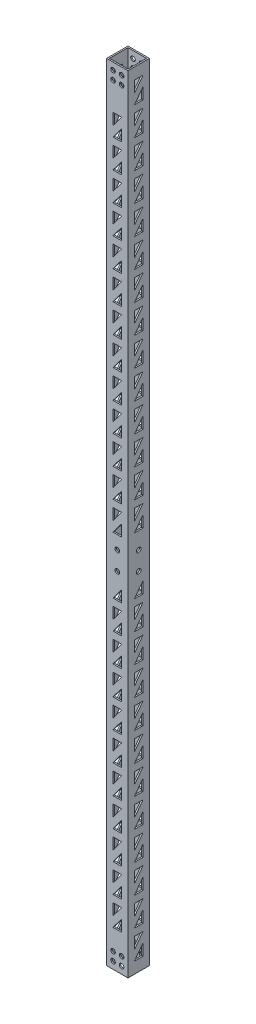
SolidWorks part; units mm, degrees
ref_plane "前视基准面" through (0, 0, 0) normal (0, 0, 1) x (1, 0, 0)
ref_plane "上视基准面" through (0, 0, 0) normal (0, 1, 0) x (1, 0, 0)
ref_plane "右视基准面" through (0, 0, 0) normal (1, 0, 0) x (0, 0, -1)
other "Configuration Table"
sketch "草图1" plane through (0, 0, 0) normal (0, 1, 0) x (1, 0, 0)
  line L1 (6.5, -6.5) -> (-6.5, -6.5)
  line L2 (6.5, -6.5) -> (6.5, 6.5)
  line L3 (6.5, 6.5) -> (-6.5, 6.5)
  line L4 (-6.5, -6.5) -> (-6.5, 6.5)
  line L5 (6.5, -6.5) -> (-6.5, 6.5) construction
  line L6 (6.5, 6.5) -> (-6.5, -6.5) construction
  line L7 (7.5, -7.5) -> (-7.5, -7.5)
  line L8 (7.5, -7.5) -> (7.5, 7.5)
  line L9 (7.5, 7.5) -> (-7.5, 7.5)
  line L10 (-7.5, -7.5) -> (-7.5, 7.5)
  line L11 (7.5, -7.5) -> (-7.5, 7.5) construction
  line L12 (7.5, 7.5) -> (-7.5, -7.5) construction
  point P0 (0, 0)
  point P6 (0, 0)
  dimension "D1" = 13
  dimension "D2" = 15
extrude "凸台-拉伸1" add sketch "草图1" along normal blind 551
sketch "草图2" plane through (0, 0, 7.5) normal (0, 0, 1) x (1, 0, 0)
  line L0 (-7.5, 543) -> (7.5, 543) construction
  line L1 (-7.5, 551) -> (-7.5, 0) construction
  line L2 (7.5, 551) -> (7.5, 0) construction
  line L3 (-7.5, 275.5) -> (7.5, 275.5) construction
  line L4 (-7.5, 551) -> (7.5, 551) construction
  line L5 (0, 549.2213) -> (0, 545.4151) construction
  line L6 (-7.5, 525.5) -> (7.5, 525.5) construction
  line L7 (-7.5, 25.5) -> (7.5, 25.5) construction
  line L8 (-3, 512.5) -> (-3, 520.5)
  line L9 (-3, 520.5) -> (3, 520.5)
  line L10 (3, 520.5) -> (-3, 512.5)
  line L11 (-3, 505.5) -> (3, 505.5)
  line L12 (3, 505.5) -> (3, 513.5)
  line L13 (3, 513.5) -> (-3, 505.5)
  line L14 (3, 500.5) -> (-3, 492.5)
  line L15 (-3, 492.5) -> (-3, 500.5)
  line L16 (-3, 500.5) -> (3, 500.5)
  line L17 (3, 493.5) -> (-3, 485.5)
  line L18 (-3, 485.5) -> (3, 485.5)
  line L19 (3, 485.5) -> (3, 493.5)
  line L20 (3, 480.5) -> (-3, 472.5)
  line L21 (-3, 472.5) -> (-3, 480.5)
  line L22 (-3, 480.5) -> (3, 480.5)
  line L23 (3, 473.5) -> (-3, 465.5)
  line L24 (-3, 465.5) -> (3, 465.5)
  line L25 (3, 465.5) -> (3, 473.5)
  line L26 (3, 460.5) -> (-3, 452.5)
  line L27 (-3, 452.5) -> (-3, 460.5)
  line L28 (-3, 460.5) -> (3, 460.5)
  line L29 (3, 453.5) -> (-3, 445.5)
  line L30 (-3, 445.5) -> (3, 445.5)
  line L31 (3, 445.5) -> (3, 453.5)
  line L32 (3, 440.5) -> (-3, 432.5)
  line L33 (-3, 432.5) -> (-3, 440.5)
  line L34 (-3, 440.5) -> (3, 440.5)
  line L35 (3, 433.5) -> (-3, 425.5)
  line L36 (-3, 425.5) -> (3, 425.5)
  line L37 (3, 425.5) -> (3, 433.5)
  line L38 (3, 420.5) -> (-3, 412.5)
  line L39 (-3, 412.5) -> (-3, 420.5)
  line L40 (-3, 420.5) -> (3, 420.5)
  line L41 (3, 413.5) -> (-3, 405.5)
  line L42 (-3, 405.5) -> (3, 405.5)
  line L43 (3, 405.5) -> (3, 413.5)
  line L44 (3, 400.5) -> (-3, 392.5)
  line L45 (-3, 392.5) -> (-3, 400.5)
  line L46 (-3, 400.5) -> (3, 400.5)
  line L47 (3, 393.5) -> (-3, 385.5)
  line L48 (-3, 385.5) -> (3, 385.5)
  line L49 (3, 385.5) -> (3, 393.5)
  line L50 (3, 380.5) -> (-3, 372.5)
  line L51 (-3, 372.5) -> (-3, 380.5)
  line L52 (-3, 380.5) -> (3, 380.5)
  line L53 (3, 373.5) -> (-3, 365.5)
  line L54 (-3, 365.5) -> (3, 365.5)
  line L55 (3, 365.5) -> (3, 373.5)
  line L56 (3, 360.5) -> (-3, 352.5)
  line L57 (-3, 352.5) -> (-3, 360.5)
  line L58 (-3, 360.5) -> (3, 360.5)
  line L59 (3, 353.5) -> (-3, 345.5)
  line L60 (-3, 345.5) -> (3, 345.5)
  line L61 (3, 345.5) -> (3, 353.5)
  line L62 (3, 340.5) -> (-3, 332.5)
  line L63 (-3, 332.5) -> (-3, 340.5)
  line L64 (-3, 340.5) -> (3, 340.5)
  line L65 (3, 333.5) -> (-3, 325.5)
  line L66 (-3, 325.5) -> (3, 325.5)
  line L67 (3, 325.5) -> (3, 333.5)
  line L68 (3, 320.5) -> (-3, 312.5)
  line L69 (-3, 312.5) -> (-3, 320.5)
  line L70 (-3, 320.5) -> (3, 320.5)
  line L71 (3, 313.5) -> (-3, 305.5)
  line L72 (-3, 305.5) -> (3, 305.5)
  line L73 (3, 305.5) -> (3, 313.5)
  line L74 (3, 300.5) -> (-3, 292.5)
  line L75 (-3, 292.5) -> (-3, 300.5)
  line L76 (-3, 300.5) -> (3, 300.5)
  line L77 (3, 293.5) -> (-3, 285.5)
  line L78 (-3, 285.5) -> (3, 285.5)
  line L79 (3, 285.5) -> (3, 293.5)
  line L80 (3, 280.5) -> (-3, 272.5)
  line L81 (-3, 272.5) -> (-3, 280.5)
  line L82 (-3, 280.5) -> (3, 280.5)
  line L83 (3, 273.5) -> (-3, 265.5)
  line L84 (-3, 265.5) -> (3, 265.5)
  line L85 (3, 265.5) -> (3, 273.5)
  line L95 (3, 233.5) -> (-3, 225.5)
  line L96 (-3, 225.5) -> (3, 225.5)
  line L97 (3, 225.5) -> (3, 233.5)
  line L98 (3, 220.5) -> (-3, 212.5)
  line L99 (-3, 212.5) -> (-3, 220.5)
  line L100 (-3, 220.5) -> (3, 220.5)
  line L101 (3, 213.5) -> (-3, 205.5)
  line L102 (-3, 205.5) -> (3, 205.5)
  line L103 (3, 205.5) -> (3, 213.5)
  line L104 (3, 200.5) -> (-3, 192.5)
  line L105 (-3, 192.5) -> (-3, 200.5)
  line L106 (-3, 200.5) -> (3, 200.5)
  line L107 (3, 193.5) -> (-3, 185.5)
  line L108 (-3, 185.5) -> (3, 185.5)
  line L109 (3, 185.5) -> (3, 193.5)
  line L110 (3, 180.5) -> (-3, 172.5)
  line L111 (-3, 172.5) -> (-3, 180.5)
  line L112 (-3, 180.5) -> (3, 180.5)
  line L113 (3, 173.5) -> (-3, 165.5)
  line L114 (-3, 165.5) -> (3, 165.5)
  line L115 (3, 165.5) -> (3, 173.5)
  line L116 (3, 160.5) -> (-3, 152.5)
  line L117 (-3, 152.5) -> (-3, 160.5)
  line L118 (-3, 160.5) -> (3, 160.5)
  line L119 (3, 153.5) -> (-3, 145.5)
  line L120 (-3, 145.5) -> (3, 145.5)
  line L121 (3, 145.5) -> (3, 153.5)
  line L122 (3, 140.5) -> (-3, 132.5)
  line L123 (-3, 132.5) -> (-3, 140.5)
  line L124 (-3, 140.5) -> (3, 140.5)
  line L125 (3, 133.5) -> (-3, 125.5)
  line L126 (-3, 125.5) -> (3, 125.5)
  line L127 (3, 125.5) -> (3, 133.5)
  line L128 (3, 120.5) -> (-3, 112.5)
  line L129 (-3, 112.5) -> (-3, 120.5)
  line L130 (-3, 120.5) -> (3, 120.5)
  line L131 (3, 113.5) -> (-3, 105.5)
  line L132 (-3, 105.5) -> (3, 105.5)
  line L133 (3, 105.5) -> (3, 113.5)
  line L134 (3, 100.5) -> (-3, 92.5)
  line L135 (-3, 92.5) -> (-3, 100.5)
  line L136 (-3, 100.5) -> (3, 100.5)
  line L137 (3, 93.5) -> (-3, 85.5)
  line L138 (-3, 85.5) -> (3, 85.5)
  line L139 (3, 85.5) -> (3, 93.5)
  line L140 (3, 80.5) -> (-3, 72.5)
  line L141 (-3, 72.5) -> (-3, 80.5)
  line L142 (-3, 80.5) -> (3, 80.5)
  line L143 (3, 73.5) -> (-3, 65.5)
  line L144 (-3, 65.5) -> (3, 65.5)
  line L145 (3, 65.5) -> (3, 73.5)
  line L146 (3, 60.5) -> (-3, 52.5)
  line L147 (-3, 52.5) -> (-3, 60.5)
  line L148 (-3, 60.5) -> (3, 60.5)
  line L149 (3, 53.5) -> (-3, 45.5)
  line L150 (-3, 45.5) -> (3, 45.5)
  line L151 (3, 45.5) -> (3, 53.5)
  line L152 (3, 40.5) -> (-3, 32.5)
  line L153 (-3, 32.5) -> (-3, 40.5)
  line L154 (-3, 40.5) -> (3, 40.5)
  line L155 (3, 33.5) -> (-3, 25.5)
  line L156 (-3, 25.5) -> (3, 25.5)
  line L157 (3, 25.5) -> (3, 33.5)
  line L158 (3, 253.5) -> (-3, 245.5) [skipped]
  line L159 (3, 245.5) -> (3, 253.5) [skipped]
  line L160 (-3, 245.5) -> (3, 245.5) [skipped]
  line L161 (-3, 252.5) -> (-3, 260.5) [skipped]
  line L162 (-3, 260.5) -> (3, 260.5) [skipped]
  line L163 (3, 260.5) -> (-3, 252.5) [skipped]
  line L164 (-3, 232.5) -> (-3, 240.5) [skipped]
  line L165 (-3, 240.5) -> (3, 240.5) [skipped]
  line L166 (3, 240.5) -> (-3, 232.5) [skipped]
  circle A0 centre (-3, 546) radius 1.6
  circle A1 centre (3, 546) radius 1.6
  circle A2 centre (-3, 540) radius 1.6
  circle A3 centre (3, 540) radius 1.6
  circle A4 centre (3, 11) radius 1.6
  circle A5 centre (-3, 11) radius 1.6
  circle A6 centre (3, 5) radius 1.6
  circle A7 centre (-3, 5) radius 1.6
  circle A9 centre (0, 256.2) radius 1.6
  circle A10 centre (0, 243.2) radius 1.6
  dimension "D2" = 3.2
  dimension "D6" = 3.2
  dimension "D1" = 8
  dimension "D3" = 6
  dimension "D4" = 6
  dimension "D5" = 25.5
  dimension "D7" = 294.8
  dimension "D8" = 13
  dimension "D9" = 6
  dimension "D10" = 8
  dimension "D11" = 5
  dimension "D12" = 8
  dimension "D13" = 6
  dimension "D14" = 15
  dimension "D15" = 25
extrude "切除-拉伸1" cut sketch "草图2" against normal up to surface (15 mm away) up to face at (0, 275.5, -7.5)
sketch "草图4" plane through (7.5, 0, 0) normal (1, 0, 0) x (0, 0, -1)
  line L0 (0, 279.6032) -> (0, 248.1841) construction
  line L1 (-7.5, 551) -> (7.5, 551) construction
  line L2 (-3, 543) -> (3, 543)
  line L3 (3, 543) -> (-3, 535)
  line L4 (-3, 535) -> (-3, 543)
  line L5 (-3, 528) -> (3, 536)
  line L6 (3, 536) -> (3, 528)
  line L7 (3, 528) -> (-3, 528)
  line L8 (-3, 515) -> (-3, 523)
  line L9 (-3, 523) -> (3, 523)
  line L10 (3, 523) -> (-3, 515)
  line L11 (3, 508) -> (-3, 508)
  line L12 (-3, 508) -> (3, 516)
  line L13 (3, 516) -> (3, 508)
  line L14 (-3, 495) -> (-3, 503)
  line L15 (-3, 503) -> (3, 503)
  line L16 (3, 503) -> (-3, 495)
  line L17 (3, 488) -> (-3, 488)
  line L18 (-3, 488) -> (3, 496)
  line L19 (3, 496) -> (3, 488)
  line L20 (-3, 475) -> (-3, 483)
  line L21 (-3, 483) -> (3, 483)
  line L22 (3, 483) -> (-3, 475)
  line L23 (3, 468) -> (-3, 468)
  line L24 (-3, 468) -> (3, 476)
  line L25 (3, 476) -> (3, 468)
  line L26 (-3, 455) -> (-3, 463)
  line L27 (-3, 463) -> (3, 463)
  line L28 (3, 463) -> (-3, 455)
  line L29 (3, 448) -> (-3, 448)
  line L30 (-3, 448) -> (3, 456)
  line L31 (3, 456) -> (3, 448)
  line L32 (-3, 435) -> (-3, 443)
  line L33 (-3, 443) -> (3, 443)
  line L34 (3, 443) -> (-3, 435)
  line L35 (3, 428) -> (-3, 428)
  line L36 (-3, 428) -> (3, 436)
  line L37 (3, 436) -> (3, 428)
  line L38 (-3, 415) -> (-3, 423)
  line L39 (-3, 423) -> (3, 423)
  line L40 (3, 423) -> (-3, 415)
  line L41 (3, 408) -> (-3, 408)
  line L42 (-3, 408) -> (3, 416)
  line L43 (3, 416) -> (3, 408)
  line L44 (-3, 395) -> (-3, 403)
  line L45 (-3, 403) -> (3, 403)
  line L46 (3, 403) -> (-3, 395)
  line L47 (3, 388) -> (-3, 388)
  line L48 (-3, 388) -> (3, 396)
  line L49 (3, 396) -> (3, 388)
  line L50 (-3, 375) -> (-3, 383)
  line L51 (-3, 383) -> (3, 383)
  line L52 (3, 383) -> (-3, 375)
  line L53 (3, 368) -> (-3, 368)
  line L54 (-3, 368) -> (3, 376)
  line L55 (3, 376) -> (3, 368)
  line L56 (-3, 355) -> (-3, 363)
  line L57 (-3, 363) -> (3, 363)
  line L58 (3, 363) -> (-3, 355)
  line L59 (3, 348) -> (-3, 348)
  line L60 (-3, 348) -> (3, 356)
  line L61 (3, 356) -> (3, 348)
  line L62 (-3, 335) -> (-3, 343)
  line L63 (-3, 343) -> (3, 343)
  line L64 (3, 343) -> (-3, 335)
  line L65 (3, 328) -> (-3, 328)
  line L66 (-3, 328) -> (3, 336)
  line L67 (3, 336) -> (3, 328)
  line L68 (-3, 315) -> (-3, 323)
  line L69 (-3, 323) -> (3, 323)
  line L70 (3, 323) -> (-3, 315)
  line L71 (3, 308) -> (-3, 308)
  line L72 (-3, 308) -> (3, 316)
  line L73 (3, 316) -> (3, 308)
  line L74 (-3, 295) -> (-3, 303)
  line L75 (-3, 303) -> (3, 303)
  line L76 (3, 303) -> (-3, 295)
  line L77 (3, 288) -> (-3, 288)
  line L78 (-3, 288) -> (3, 296)
  line L79 (3, 296) -> (3, 288)
  line L80 (-3, 275) -> (-3, 283)
  line L81 (-3, 283) -> (3, 283)
  line L82 (3, 283) -> (-3, 275)
  line L83 (3, 268) -> (-3, 268)
  line L84 (-3, 268) -> (3, 276)
  line L85 (3, 276) -> (3, 268)
  line L95 (3, 228) -> (-3, 228)
  line L96 (-3, 228) -> (3, 236)
  line L97 (3, 236) -> (3, 228)
  line L98 (-3, 215) -> (-3, 223)
  line L99 (-3, 223) -> (3, 223)
  line L100 (3, 223) -> (-3, 215)
  line L101 (3, 208) -> (-3, 208)
  line L102 (-3, 208) -> (3, 216)
  line L103 (3, 216) -> (3, 208)
  line L104 (-3, 195) -> (-3, 203)
  line L105 (-3, 203) -> (3, 203)
  line L106 (3, 203) -> (-3, 195)
  line L107 (3, 188) -> (-3, 188)
  line L108 (-3, 188) -> (3, 196)
  line L109 (3, 196) -> (3, 188)
  line L110 (-3, 175) -> (-3, 183)
  line L111 (-3, 183) -> (3, 183)
  line L112 (3, 183) -> (-3, 175)
  line L113 (3, 168) -> (-3, 168)
  line L114 (-3, 168) -> (3, 176)
  line L115 (3, 176) -> (3, 168)
  line L116 (-3, 155) -> (-3, 163)
  line L117 (-3, 163) -> (3, 163)
  line L118 (3, 163) -> (-3, 155)
  line L119 (3, 148) -> (-3, 148)
  line L120 (-3, 148) -> (3, 156)
  line L121 (3, 156) -> (3, 148)
  line L122 (-3, 135) -> (-3, 143)
  line L123 (-3, 143) -> (3, 143)
  line L124 (3, 143) -> (-3, 135)
  line L125 (3, 128) -> (-3, 128)
  line L126 (-3, 128) -> (3, 136)
  line L127 (3, 136) -> (3, 128)
  line L128 (-3, 115) -> (-3, 123)
  line L129 (-3, 123) -> (3, 123)
  line L130 (3, 123) -> (-3, 115)
  line L131 (3, 108) -> (-3, 108)
  line L132 (-3, 108) -> (3, 116)
  line L133 (3, 116) -> (3, 108)
  line L134 (-3, 95) -> (-3, 103)
  line L135 (-3, 103) -> (3, 103)
  line L136 (3, 103) -> (-3, 95)
  line L137 (3, 88) -> (-3, 88)
  line L138 (-3, 88) -> (3, 96)
  line L139 (3, 96) -> (3, 88)
  line L140 (-3, 75) -> (-3, 83)
  line L141 (-3, 83) -> (3, 83)
  line L142 (3, 83) -> (-3, 75)
  line L143 (3, 68) -> (-3, 68)
  line L144 (-3, 68) -> (3, 76)
  line L145 (3, 76) -> (3, 68)
  line L146 (-3, 55) -> (-3, 63)
  line L147 (-3, 63) -> (3, 63)
  line L148 (3, 63) -> (-3, 55)
  line L149 (3, 48) -> (-3, 48)
  line L150 (-3, 48) -> (3, 56)
  line L151 (3, 56) -> (3, 48)
  line L152 (-3, 35) -> (-3, 43)
  line L153 (-3, 43) -> (3, 43)
  line L154 (3, 43) -> (-3, 35)
  line L155 (3, 28) -> (-3, 28)
  line L156 (-3, 28) -> (3, 36)
  line L157 (3, 36) -> (3, 28)
  line L158 (-3, 15) -> (-3, 23)
  line L159 (-3, 23) -> (3, 23)
  line L160 (3, 23) -> (-3, 15)
  line L161 (3, 8) -> (-3, 8)
  line L162 (-3, 8) -> (3, 16)
  line L163 (3, 16) -> (3, 8)
  line L166 (-3, 255) -> (-3, 263) [skipped]
  line L167 (-3, 263) -> (3, 263) [skipped]
  line L168 (3, 263) -> (-3, 255) [skipped]
  line L169 (-3, 248) -> (3, 256) [skipped]
  line L170 (3, 256) -> (3, 248) [skipped]
  line L171 (3, 248) -> (-3, 248) [skipped]
  line L172 (-3, 243) -> (3, 243) [skipped]
  line L173 (3, 243) -> (-3, 235) [skipped]
  line L174 (-3, 235) -> (-3, 243) [skipped]
  circle A0 centre (0, 256.2) radius 1.6
  circle A1 centre (0, 243.2) radius 1.6
  point P14 (0, 528)
  dimension "D1" = 3.2
  dimension "D2" = 294.8
  dimension "D3" = 13
  dimension "D4" = 3
  dimension "D5" = 3
  dimension "D6" = 8
  dimension "D7" = 8
  dimension "D8" = 6
  dimension "D9" = 8
  dimension "D10" = 15
  dimension "D11" = 3
  dimension "D13" = 20
  dimension "D12" = 27
extrude "切除-拉伸2" cut sketch "草图4" against normal up to surface (15 mm away) up to face at (-7.5, 275.5, 0)
